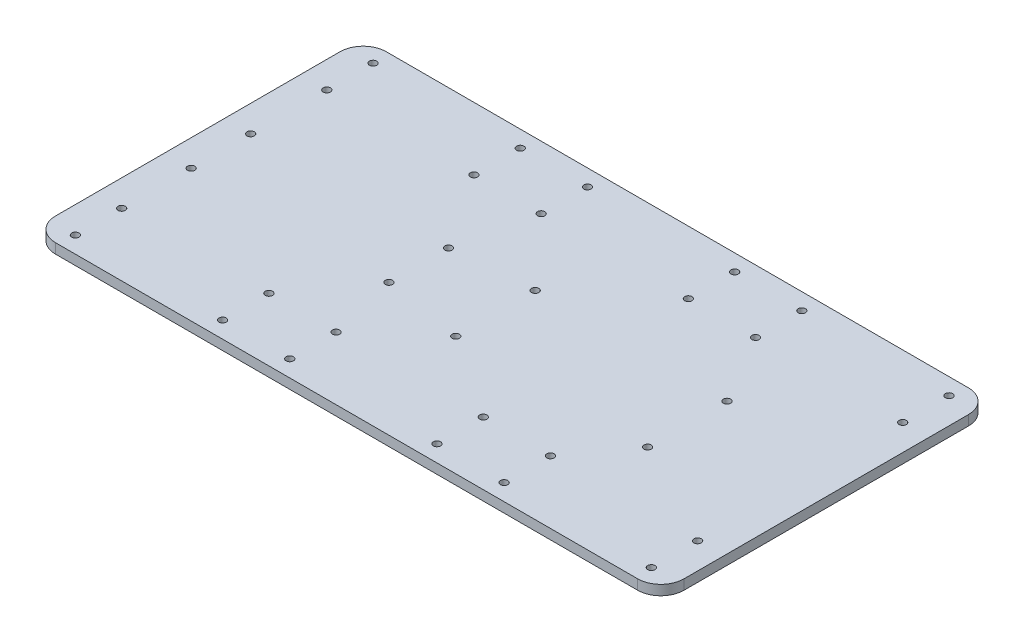
SolidWorks part; units mm, degrees
ref_plane "Front Plane" through (0, 0, 0) normal (0, 0, 1) x (1, 0, 0)
ref_plane "Top Plane" through (0, 0, 0) normal (0, 1, 0) x (1, 0, 0)
ref_plane "Right Plane" through (0, 0, 0) normal (1, 0, 0) x (0, 0, -1)
sketch "Sketch1" plane through (0, 0, 0) normal (0, 1, 0) x (1, 0, 0)
  line L1 (0, 0) -> (190, 0)
  line L2 (0, 0) -> (0, 100)
  line L3 (0, 100) -> (190, 100)
  line L4 (190, 0) -> (190, 100)
  dimension "D1" = 190
  dimension "D2" = 100
extrude "Boss-Extrude1" add sketch "Sketch1" along normal blind 3
hole_wizard "Tap Drill for M2.5x0.45 Tap1" positions "Sketch3" profile "Sketch4" hole size "M2.5x0.45" standard "ANSI Metric" end condition through all
sketch "Sketch3" plane through (0, 3, 0) normal (0, 1, 0) x (1, 0, 0)
  line L1 (190, 100) -> (0, 100) construction
  line L2 (0, 100) -> (0, 0) construction
  line L3 (0, 50) -> (190, 50) construction
  line L4 (190, 0) -> (190, 100) construction
  line L5 (0, 0) -> (190, 0) construction
  point P0 (8, 95)
  point P2 (52.5, 95)
  point P4 (52.5, 81)
  point P6 (8, 81)
  point P32 (52.5, 19)
  point P33 (52.5, 5)
  point P34 (8, 19)
  point P35 (8, 5)
  point P45 (72.811, 95)
  point P46 (117.311, 95)
  point P47 (117.311, 81)
  point P48 (72.811, 81)
  point P49 (137.622, 95)
  point P50 (182.122, 95)
  point P51 (182.122, 81)
  point P52 (137.622, 81)
  point P54 (72.811, 19)
  point P55 (117.311, 19)
  point P56 (137.622, 19)
  point P57 (182.122, 19)
  point P58 (182.122, 5)
  point P59 (137.622, 5)
  point P60 (117.311, 5)
  point P61 (72.811, 5)
  point P64 (8, 58)
  point P66 (8, 40)
  point P68 (67.78, 58)
  point P70 (67.78, 40)
  point P72 (92, 60)
  point P74 (92, 36)
  point P76 (150, 36)
  point P78 (150, 60)
  point P86 (92, 56)
  dimension "D1" = 14
  dimension "D2" = 5
  dimension "D3" = 5
  dimension "D4" = 44.5
  dimension "D5" = 8
  dimension "D7" = 20.311
  dimension "D8" = 18
  dimension "D9" = 59.78
  dimension "D10" = 24
  dimension "D11" = 58
  dimension "D12" = 8
  dimension "D13" = 40
  dimension "D14" = 40
  dimension "D15" = 60
  dimension "D6" = 3
sketch "Sketch4" plane through (8, 3, -95) normal (1, 0, 0) x (0, 0, 1)
  line L0 (0, 0) -> (0, 3)
  line L1 (0, 3) -> (1.1, 3)
  line L2 (1.1, 3) -> (1.1, 0)
  line L5 (1.1, 0) -> (0, 0)
  line L11 (0, -6.35) -> (0, 107.95) construction
  dimension "Thru Hole Dia." = 2.2
  dimension "Thru Hole Depth" = 3
fillet "Fillet1" radius 7 4 edges at (190, 1.5, -100) (190, 1.5, 0) (0, 1.5, 0) (0, 1.5, -100)
